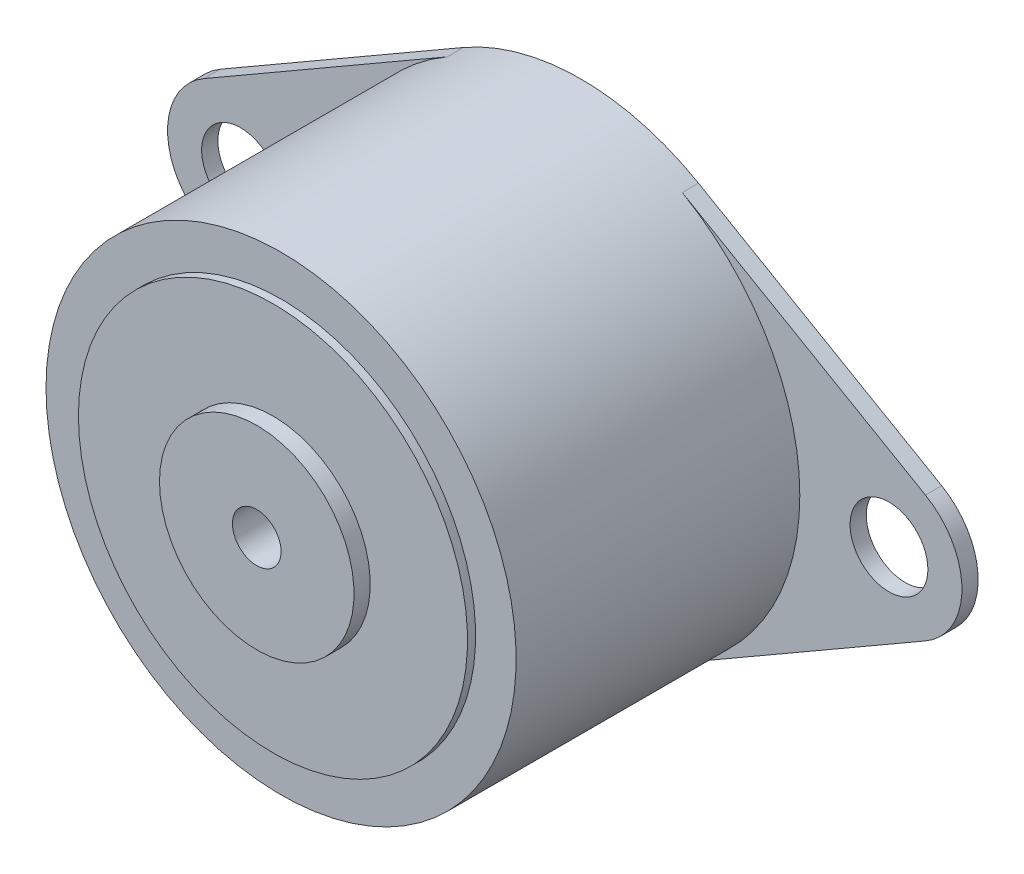
SolidWorks part; units mm, degrees
ref_plane "Plan de face" through (0, 0, 0) normal (0, 0, 1) x (1, 0, 0)
ref_plane "Plan de dessus" through (0, 0, 0) normal (0, 1, 0) x (1, 0, 0)
ref_plane "Plan de droite" through (0, 0, 0) normal (1, 0, 0) x (0, 0, -1)
sketch "Esquisse1" plane through (0, 0, 0) normal (0, 0, 1) x (1, 0, 0)
  line L0 (-21.4452, 0) -> (24.3417, 0) construction
  line L1 (0, 0) -> (0, 12.3393) construction
  line L2 (-11.125, 1.9486) -> (-3.625, 6.2787)
  line L3 (11.125, 1.9486) -> (3.625, 6.2787)
  line L4 (11.125, -1.9486) -> (3.625, -6.2787)
  line L5 (-11.125, -1.9486) -> (-3.625, -6.2787)
  arc A0 (3.625, 6.2787) -> (-3.625, 6.2787) centre (0, 0) ccw
  arc A1 (-11.125, 1.9486) -> (-11.125, -1.9486) centre (-10, 0) ccw
  arc A2 (11.125, 1.9486) -> (11.125, -1.9486) centre (10, 0) cw
  arc A3 (3.625, -6.2787) -> (-3.625, -6.2787) centre (0, 0) cw
  dimension "D1" = 14.5
  dimension "D5" = 4.5
  dimension "D2" = 10
extrude "Boss.-Extru.1" add sketch "Esquisse1" along normal blind 0.5
sketch "Esquisse2" plane through (0, 0, 0.5) normal (0, 0, 1) x (1, 0, 0)
  circle A0 centre (0, 0) radius 7.25
  circle A1 centre (0, 0) radius 7
  dimension "D1" = 0.25
extrude "Boss.-Extru.2" add sketch "Esquisse2" along normal blind 8
ref_plane "Plan1" through (-4.9518, -4.9518, 0) normal (-0.7071, -0.7071, 0) x (0, 0, -1)
sketch "Esquisse8" plane through (-4.9518, -4.9518, 0) normal (-0.7071, -0.7071, 0) x (0, 0, -1)
  line L1 (-11.5389, 2.5) -> (-4, 2.5)
  line L2 (-11.5389, 2.5) -> (-11.5389, -2.5)
  line L3 (-11.5389, -2.5) -> (-4, -2.5)
  line L4 (-4, 2.5) -> (-4, -2.5)
  dimension "D1" = 4
  dimension "D2" = 5
  dimension "D3" = 2.5
hole_wizard "Dégagement M21" positions "Esquisse3D1" profile "Esquisse3" hole size "M2" standard "ISO"
sketch3d "Esquisse3D1"
  line L0 (-10, 0, 0.5) -> (-10, 0, 0) construction
  line L1 (10, 0, 0.5) -> (10, 0, 0) construction
  point P0 (-10, 0, 0.5)
  point P4 (10, 0, 0.5)
sketch "Esquisse3" plane through (-10, 0, 0.5) normal (1, 0, 0) x (0, -1, 0)
  line L0 (0, 0) -> (0, 10.721)
  line L1 (0, 10.721) -> (1.2, 10)
  line L2 (1.2, 10) -> (1.2, 0)
  line L5 (1.2, 0) -> (0, 0)
  line L10 (0, 10.721) -> (-1.2, 10) construction
  line L11 (0, -6.35) -> (0, 107.95) construction
  dimension "Diamètre du perçage" = 2.4
  dimension "Profondeur du perçage" = 10
  dimension "Angle de pointe" = 118
sketch "Esquisse5" plane through (0, 0, 0) normal (0, 1, 0) x (1, 0, 0)
  line L0 (0, 0) -> (0, -11.9683) construction
  line L1 (-6, -9.25) -> (-6, -9.5)
  line L3 (-6, -9.5) -> (-3, -9.5)
  line L4 (-3, -9.5) -> (-3, -10)
  line L5 (-3, -10) -> (-0.75, -10)
  line L6 (-0.75, -10) -> (-0.75, -9.25)
  line L7 (-6, -9.25) -> (-0.75, -9.25)
  line L8 (-7.25, -8.5) -> (7.25, -8.5) construction
  dimension "D1" = 0.75
  dimension "D2" = 0.75
  dimension "D3" = 3
  dimension "D4" = 0.5
  dimension "D5" = 6
  dimension "D6" = 0.75
revolve "Révolution1" add sketch "Esquisse5" angle 360 about L0
sketch "Esquisse16" plane through (0, 0, 8.5) normal (0, 0, 1) x (1, 0, 0)
  circle A0 centre (0, 0) radius 7.25
extrude "Boss.-Extru.4" add sketch "Esquisse16" along normal up to surface (0.75 mm away) up to face at (-6, 0, 9.25)
sketch "Esquisse7" plane through (0, 0, 0) normal (0, 0, -1) x (-1, 0, 0)
  circle A0 centre (0, 0) radius 0.75
  dimension "D1" = 1.5
extrude "Enlèv. mat.-Extru.1" cut sketch "Esquisse7" against normal through all
